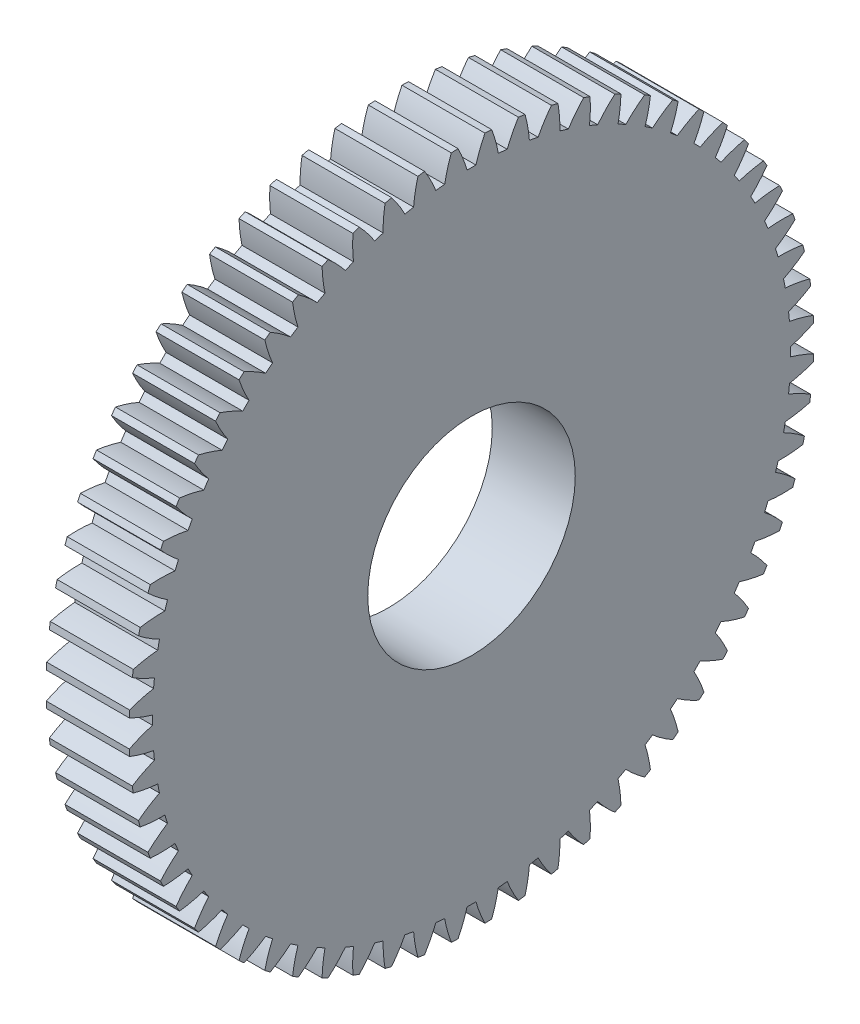
SolidWorks part; units mm, degrees
ref_plane "Plane1" through (0, 0, 0) normal (0, 0, 1) x (1, 0, 0)
ref_plane "Plane2" through (0, 0, 0) normal (0, 1, 0) x (1, 0, 0)
ref_plane "Plane3" through (0, 0, 0) normal (1, 0, 0) x (0, 0, -1)
sketch "HoldingSke" plane through (0, 0, 0) normal (0, 1, 0) x (1, 0, 0)
  line L0 (0, 0) -> (0.8767, -1.7976)
  line L1 (-15, 0) -> (100, 0) construction
  line L2 (0, 0) -> (-2.1039, 2.3779)
  line L3 (0, 0) -> (-11.863, 4.5341)
  line L4 (0, 0) -> (3.7858, 7.762)
  line L5 (0, 0) -> (-46.8476, -17.4728)
  line L6 (0, 0) -> (-3.3159, -2.2372)
  line L7 (-2.1039, 2.3779) -> (8.6586, 51.2059)
  line L8 (-76.2, 54.61) -> (-74.4, 54.61)
  line L9 (-71.009, 38.7566) -> (-53.1078, 45.2721)
  line L10 (-76.2, 71.12) -> (104.1128, 71.12)
  line L11 (0, 0) -> (-4, 0)
  line L12 (-76.2, 101.6) -> (-76.181, 101.6)
  line L13 (24.9733, 27.94) -> (52.9518, 28.4284)
  line L14 (24.9733, 27.94) -> (24.9743, 27.94)
  line L15 (24.9733, 27.94) -> (100.4006, 29.5858)
  line L16 (-63.627, -0.5) -> (-12.827, -0.5)
  circle A0 centre (0, 0) radius 5
  circle A1 centre (0, 0) radius 15.374
  circle A2 centre (0, 0) radius 37.5
  circle A3 centre (0, 0) radius 5
  dimension "MHD" = 30.748
  dimension "Hub_dia" = 75
  dimension "Bore" = 10
  dimension "MBD" = 10
  dimension "Num_teeth" = 64
  dimension "Pitch" = 2
  dimension "Overall_len" = 50
  dimension "Show_teeth" = 64
  dimension "Thickness" = 4
  dimension "OAL" = 50.0001
  dimension "T_dim" = 1.8
  dimension "Ap" = 20
  dimension "H" = 19.05
  dimension "Pitch_radius" = 180.3128
  dimension "Width" = 4
  dimension "Backlash" = 0.019
  dimension "Addendum_fac" = 1
  dimension "Dedendum_fac" = 1.25
  dimension "Clearance_fac" = 0.25
  dimension "Dedendum_add" = 0.001
  dimension "Module" = 0.5
sketch "BasProSke" plane through (0, 0, 0) normal (0, 1, 0) x (1, 0, 0)
  line L0 (-10, 0) -> (60, 0) construction
  line L1 (0, 0) -> (0, 16.5)
  line L2 (0, 0) -> (4, 0)
  line L3 (4, 0) -> (4, 16.5)
  line L4 (4, 16.5) -> (0, 16.5)
  dimension "Thickness" = 4
  dimension "Diameter" = 33
revolve "Base-Revolve" add sketch "BasProSke" angle 360 about L0
sketch "TooCutSke" plane through (0, 0, 0) normal (1, 0, 0) x (0, 0, -1)
  line L1 (0, 0) -> (0, 107) construction
  line L2 (0, 0) -> (-0.4259, 15.9943) construction
  line L3 (0, 0) -> (-1.5698, 31.9534) construction
  line L4 (-0.4259, 15.9943) -> (-0.7849, 15.9767) construction
  arc A0 (0.2137, 15.3725) -> (-0.2137, 15.3725) centre (0, 0) ccw
  arc A1 (0.66, 16.5122) -> (-0.66, 16.5122) centre (0, 0) ccw
  circle A2 centre (0, 0) radius 16 construction
  circle A3 centre (0, 0) radius 15.0351 construction
  arc A4 (-0.2137, 15.3725) -> (-0.66, 16.5122) centre (-6.369, 13.6195) ccw
  arc A5 (0.66, 16.5122) -> (0.2137, 15.3725) centre (6.369, 13.6195) ccw
  dimension "Root_dia" = 30.748
  dimension "Overcut_dia" = 33.0508
  dimension "Pitch_dia" = 32
  dimension "Base_dia" = 30.0702
  dimension "Flank_rad" = 6.4
  dimension "Half_ang" = 2.813
  dimension "Half_CT" = 0.3594
extrude "ToothCut" cut sketch "TooCutSke" along normal through all
fillet "Breaks" [suppressed] radius 0.01
fillet "RootFillets" [suppressed] radius 0.126
pattern_circular "TeethCuts" count 64 every 5.625 about axis through (-10, 0, 0) along (1, 0, 0) of "ToothCut", "RootFillets", "Breaks"
sketch "HubNeaOneSke" plane through (0, 0, 0) normal (-1, 0, 0) x (0, 0, 1)
  circle A0 centre (0, 0) radius 15.374
  dimension "Diameter" = 30.748
extrude "HubNearOne" [suppressed] add sketch "HubNeaOneSke" along normal blind 46.0001
sketch "HubNeaBotSke" plane through (0, 0, 0) normal (-1, 0, 0) x (0, 0, 1)
  circle A0 centre (0, 0) radius 15.374
  dimension "Diameter" = 30.748
extrude "HubNearBoth" [suppressed] add sketch "HubNeaBotSke" along normal blind 23
ref_plane "FarPln" through (4, 0, 0) normal (1, 0, 0) x (0, 0, -1)
sketch "HubFarSke" plane through (4, 0, 0) normal (1, 0, 0) x (0, 0, -1)
  circle A0 centre (0, 0) radius 15.374
  dimension "Diameter" = 30.748
extrude "HubFar" [suppressed] add sketch "HubFarSke" along normal blind 23
sketch "BorSke" plane through (0, 0, 0) normal (1, 0, 0) x (0, 0, -1)
  circle A0 centre (0, 0) radius 5
  dimension "Diameter" = 10
extrude "Bore" cut sketch "BorSke" along normal mid plane 100.0001
sketch "KeySke" plane through (0, 0, 0) normal (1, 0, 0) x (0, 0, -1)
  line L0 (-2, 0) -> (-2, 6.8)
  line L1 (-2, 6.8) -> (2, 6.8)
  line L2 (2, 6.8) -> (2, 0)
  line L3 (0, 0) -> (0, 34) construction
  line L4 (-2, 0) -> (2, 0)
  dimension "Width" = 4
  dimension "Offset" = 6.8
extrude "Keyway" [suppressed] cut sketch "KeySke" along normal mid plane 100.0001
pattern_circular "Keyway2" [suppressed] count 2 every 90 about axis through (-10, 0, 0) along (1, 0, 0)
equation "' \"Module@HoldingSke\" = 6.35"
equation "' \"Num_teeth@HoldingSke\" = 12"
equation "' \"Ap@HoldingSke\" =  20"
equation "' \"Ap@HoldingSke\" = 20"
equation "' \"Width@HoldingSke\" = 0.5 * 25.4"
equation "' \"Hub_dia@HoldingSke\"= 1 * 25.4"
equation "' \"Hub_dia@HoldingSke\" = 1 * 25.4"
equation "' \"Overall_len@HoldingSke\" = 1.0 * 25.4"
equation "' \"Bore@HoldingSke\" = 0.75 * 25.4"
equation "' \"T_dim@HoldingSke\" = 0.1 * 25.4"
equation "' \"Width@KeySke\" = 0.25 * 25.4"
equation "' \"Show_teeth@HoldingSke\" = 13"
equation "' \"Backlash@HoldingSke\" = 0.009 * 25.4"
equation "' \"Addendum_fac@HoldingSke\" = 1.0"
equation "' \"Dedendum_fac@HoldingSke\" = 1.25"
equation "' \"Dedendum_add@HoldingSke\" = 0.00005 * 25.4"
equation "' \"Clearance_fac@HoldingSke\" = 0.25"
equation "\"Pitch@HoldingSke\" = 1 / \"Module@HoldingSke\""
equation "\"Overcut_dia@TooCutSke\" = (\"Num_teeth@HoldingSke\" + 2 * \"Addendum_fac@HoldingSke\") / \"Pitch@HoldingSke\" + 0.002 * 25.4"
equation "\"Pitch_dia@TooCutSke\" = \"Num_teeth@HoldingSke\" / \"Pitch@HoldingSke\""
equation "\"Base_dia@TooCutSke\" = \"Num_teeth@HoldingSke\" / \"Pitch@HoldingSke\" * cos((\"Ap@HoldingSke\"  * 3.14159265 / 180))"
equation "\"Root_dia@TooCutSke\" = (\"Num_teeth@HoldingSke\" + 2) / \"Pitch@HoldingSke\" - 2 * (\"Addendum_fac@HoldingSke\" + \"Dedendum_fac@HoldingSke\") / \"Pitch@HoldingSke\" - \"Dedendum_add@HoldingSke\" * 2"
equation "\"Half_ang@TooCutSke\" = 180 / \"Num_teeth@HoldingSke\""
equation "\"Half_CT@TooCutSke\" = \"Num_teeth@HoldingSke\" / \"Pitch@HoldingSke\" * sin((3.14159265 / 2 / \"Num_teeth@HoldingSke\")) / 2 - 7 * \"Backlash@HoldingSke\" / 4"
equation "\"Flank_rad@TooCutSke\" = \"Num_teeth@HoldingSke\" / \"Pitch@HoldingSke\" / 5"
equation "\"Radius@RootFillets\" = \"Clearance_fac@HoldingSke\" / \"Pitch@HoldingSke\" + \"Dedendum_add@HoldingSke\""
equation "\"Break_rad@Breaks\" = 0.02 / \"Pitch@HoldingSke\""
equation "\"Thickness@HoldingSke\" = \"Width@HoldingSke\""
equation "\"OAL@HoldingSke\" = \"Thickness@HoldingSke\""
equation "\"MHD@HoldingSke\" = (\"Num_teeth@HoldingSke\" + 2) / \"Pitch@HoldingSke\" - 2 * (\"Addendum_fac@HoldingSke\" + \"Dedendum_fac@HoldingSke\")  / \"Pitch@HoldingSke\" - \"Dedendum_add@HoldingSke\" * 2"
equation "\"MBD@HoldingSke\" = (\"Num_teeth@HoldingSke\" + 2) / \"Pitch@HoldingSke\" - 2 * (\"Addendum_fac@HoldingSke\" + \"Dedendum_fac@HoldingSke\")  / \"Pitch@HoldingSke\" - \"Dedendum_add@HoldingSke\" * 2 - 0.002 * 25.4"
equation "\"MHD@HoldingSke\" = ((sgn( \"MHD@HoldingSke\" - \"Hub_dia@HoldingSke\" )-1)*( \"MHD@HoldingSke\" - \"Hub_dia@HoldingSke\" ))/-2+ \"Hub_dia@HoldingSke\""
equation "\"MBD@HoldingSke\" = ((sgn( \"MBD@HoldingSke\" - \"Bore@HoldingSke\" )-1)*( \"MBD@HoldingSke\" - \"Bore@HoldingSke\" ))/-2+ \"Bore@HoldingSke\""
equation "\"OAL@HoldingSke\" = ((sgn( \"OAL@HoldingSke\" - \"Overall_len@HoldingSke\" )+1)*( \"OAL@HoldingSke\" - \"Overall_len@HoldingSke\" ))/2 + \"Overall_len@HoldingSke\" + 0.000002 * 25.4"
equation "\"Num_teeth@TeethCuts\" = int( \"Show_teeth@HoldingSke\" ) + 1"
equation "\"Num_teeth@TeethCuts\" = ((sgn( \"Num_teeth@TeethCuts\" - \"Num_teeth@HoldingSke\" )-1)*( \"Num_teeth@TeethCuts\" - \"Num_teeth@HoldingSke\" ))/-2+ \"Num_teeth@HoldingSke\""
equation "\"Num_teeth@TeethCuts\" = ((sgn( \"Num_teeth@TeethCuts\" - 2.0)+1)*( \"Num_teeth@TeethCuts\" - 2.0))/2 +2.0"
equation "\"Angle@TeethCuts\" = 360.0 / \"Num_teeth@HoldingSke\""
equation "\"Diameter@BasProSke\" = (\"Num_teeth@HoldingSke\" + 2 * \"Addendum_fac@HoldingSke\") / \"Pitch@HoldingSke\""
equation "\"Thickness@BasProSke\"  = \"Thickness@HoldingSke\""
equation "' \"Fillet_rad@BasProSke\" =  \"Thickness@HoldingSke\" * 0.05"
equation "' \"Fillet_rad@BasProSke\" = \"Thickness@HoldingSke\" * 0.05"
equation "\"MHD@HoldingSke\" = ((sgn( \"MHD@HoldingSke\" - \"Root_dia@TooCutSke\" )-1)*( \"MHD@HoldingSke\" - \"Root_dia@TooCutSke\" ))/-2+ \"Root_dia@TooCutSke\""
equation "\"Diameter@HubNeaOneSke\" = \"MHD@HoldingSke\""
equation "\"Length@HubNearOne\" = \"OAL@HoldingSke\" - \"Thickness@BasProSke\""
equation "\"Diameter@HubNeaBotSke\" = \"MHD@HoldingSke\""
equation "\"Length@HubNearBoth\" = ( \"OAL@HoldingSke\" - \"Thickness@BasProSke\" ) / 2.0"
equation "\"Thickness@FarPln\" = \"Thickness@BasProSke\""
equation "\"Diameter@HubFarSke\" = \"MHD@HoldingSke\""
equation "\"Length@HubFar\" = ( \"OAL@HoldingSke\" - \"Thickness@BasProSke\" ) / 2.0"
equation "\"Diameter@BorSke\" = \"MBD@HoldingSke\""
equation "\"D1@Bore\" = \"OAL@HoldingSke\" * 2.0"
equation "\"D1@Keyway\" = \"OAL@HoldingSke\" * 2.0"
equation "\"Offset@KeySke\" = \"T_dim@HoldingSke\" + \"MBD@HoldingSke\" / 2.0"
